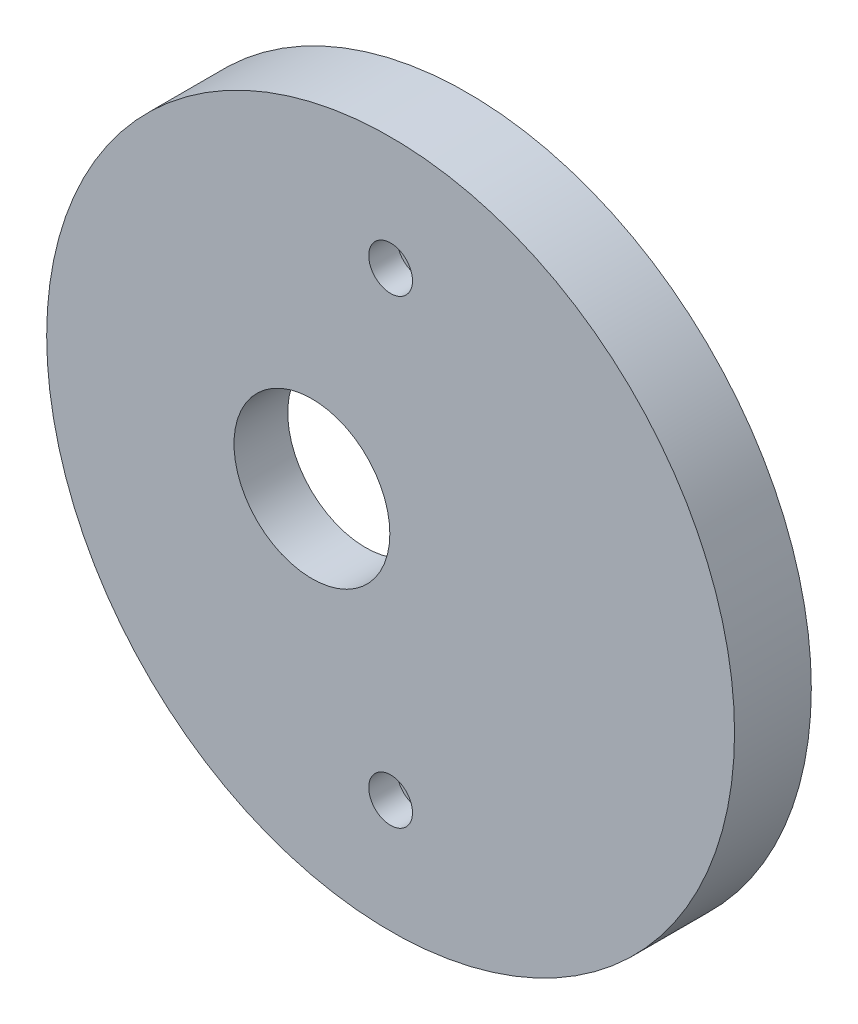
SolidWorks part; units mm, degrees
ref_plane "Plan de face" through (0, 0, 0) normal (0, 0, 1) x (1, 0, 0)
ref_plane "Plan de dessus" through (0, 0, 0) normal (0, 1, 0) x (1, 0, 0)
ref_plane "Plan de droite" through (0, 0, 0) normal (1, 0, 0) x (0, 0, -1)
sketch "Esquisse1" plane through (0, 0, 0) normal (0, 0, 1) x (1, 0, 0)
  line L0 (0, 0) -> (-44.8, 0) construction
  line L1 (0, 44.8) -> (0, -44.8) construction
  circle A0 centre (0, 0) radius 44.8
  circle A2 centre (-10.25, 0) radius 10.15
  circle A3 centre (0, 30) radius 1.8
  circle A4 centre (0, -30) radius 1.8
  dimension "D1" = 89.6
  dimension "D2" = 20.3
  dimension "D4" = 3.6
  dimension "D3" = 10.25
  dimension "D5" = 30
extrude "Boss.-Extru.1" add sketch "Esquisse1" along normal blind 7
sketch "Esquisse3" plane through (0, 0, 0) normal (0, 0, -1) x (-1, 0, 0)
  circle A1 centre (0, 0) radius 44.8
  circle A2 centre (0, 0) radius 33.5
  dimension "D1" = 67
  dimension "D2" = 89.6
extrude "Boss.-Extru.2" add sketch "Esquisse3" along normal blind 3
sketch "Esquisse4" plane through (0, 0, 7) normal (0, 0, 1) x (1, 0, 0)
  circle A0 centre (0, 30) radius 2.85
  circle A1 centre (0, -30) radius 2.85
  dimension "D1" = 5.7
  dimension "D2" = 5.7
extrude "Enlèv. mat.-Extru.3" cut sketch "Esquisse4" against normal blind 3.7
